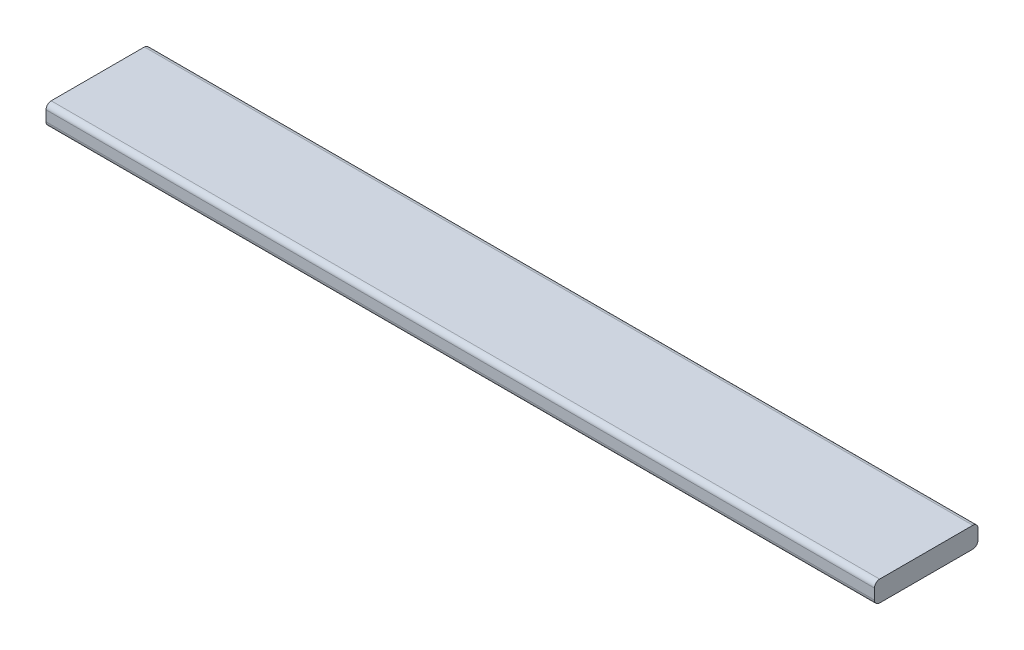
SolidWorks part; units mm, degrees
ref_plane "正面" through (0, 0, 0) normal (0, 0, 1) x (1, 0, 0)
ref_plane "平面" through (0, 0, 0) normal (0, 1, 0) x (1, 0, 0)
ref_plane "右側面" through (0, 0, 0) normal (1, 0, 0) x (0, 0, -1)
sketch "ｽｹｯﾁ1" plane through (0, 0, 0) normal (0, 1, 0) x (1, 0, 0)
  line L1 (-60, -7.5) -> (60, -7.5)
  line L2 (-60, -7.5) -> (-60, 7.5)
  line L3 (-60, 7.5) -> (60, 7.5)
  line L4 (60, -7.5) -> (60, 7.5)
  line L5 (-60, -7.5) -> (60, 7.5) construction
  line L6 (-60, 7.5) -> (60, -7.5) construction
  point P0 (0, 0)
  dimension "D1" = 15
  dimension "D2" = 120
extrude "ﾎﾞｽ - 押し出し1" add sketch "ｽｹｯﾁ1" along normal mid plane 3
fillet "ﾌｨﾚｯﾄ1" radius 0.75 4 edges at (0, -1.5, -7.5) (0, 1.5, -7.5) (0, -1.5, 7.5) (0, 1.5, 7.5)
